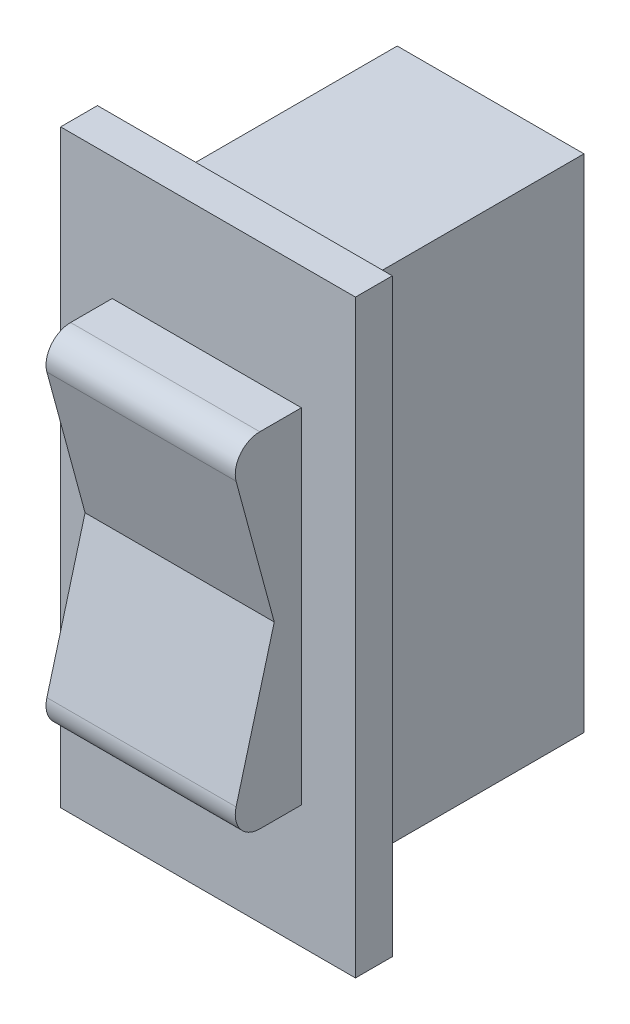
SolidWorks part; units mm, degrees
ref_plane "Front Plane" through (0, 0, 0) normal (0, 0, 1) x (1, 0, 0)
ref_plane "Top Plane" through (0, 0, 0) normal (0, 1, 0) x (1, 0, 0)
ref_plane "Right Plane" through (0, 0, 0) normal (1, 0, 0) x (0, 0, -1)
sketch "Sketch1" plane through (0, 0, 0) normal (0, 0, 1) x (1, 0, 0)
  line L1 (-3.8, -10.2) -> (3.8, -10.2)
  line L2 (-3.8, -10.2) -> (-3.8, 10.2)
  line L3 (-3.8, 10.2) -> (3.8, 10.2)
  line L4 (3.8, -10.2) -> (3.8, 10.2)
  line L5 (-3.8, -10.2) -> (3.8, 10.2) construction
  line L6 (-3.8, 10.2) -> (3.8, -10.2) construction
  point P0 (0, 0)
  dimension "D1" = 20.4
  dimension "D2" = 7.6
extrude "Boss-Extrude1" add sketch "Sketch1" along normal blind 10
sketch "Sketch2" plane through (0, 0, 10) normal (0, 0, 1) x (1, 0, 0)
  line L1 (-6, -12) -> (6, -12)
  line L2 (-6, -12) -> (-6, 12)
  line L3 (-6, 12) -> (6, 12)
  line L4 (6, -12) -> (6, 12)
  line L5 (-6, -12) -> (6, 12) construction
  line L6 (-6, 12) -> (6, -12) construction
  point P0 (0, 0)
  dimension "D1" = 12
  dimension "D2" = 24
extrude "Boss-Extrude2" add sketch "Sketch2" along normal blind 1.5
ref_plane "Plane1" through (3.8, 0, 0) normal (1, 0, 0) x (0, 0, -1)
sketch "Sketch3" plane through (3.8, 0, 0) normal (1, 0, 0) x (0, 0, -1)
  line L0 (-11.5, -12) -> (-11.5, 12) construction
  line L1 (-11.5, 7) -> (-14.5, 7)
  line L2 (-11.5, -7) -> (-14.5, -7)
  line L3 (-14.5, 7) -> (-12.6048, 0)
  line L4 (-12.6048, 0) -> (-14.5, -7)
  line L5 (-11.5, 7) -> (-11.5, -7)
  point P0 (-11.5, 7)
  point P1 (-11.5, -7)
  point P4 (-11.5, 0)
  dimension "D1" = 7
  dimension "D2" = 7
  dimension "D3" = 3
extrude "Boss-Extrude3" add sketch "Sketch3" against normal blind 7.7
fillet "Fillet1" radius 1 2 edges at (-0.05, -7, 14.5) (-0.05, 7, 14.5)
